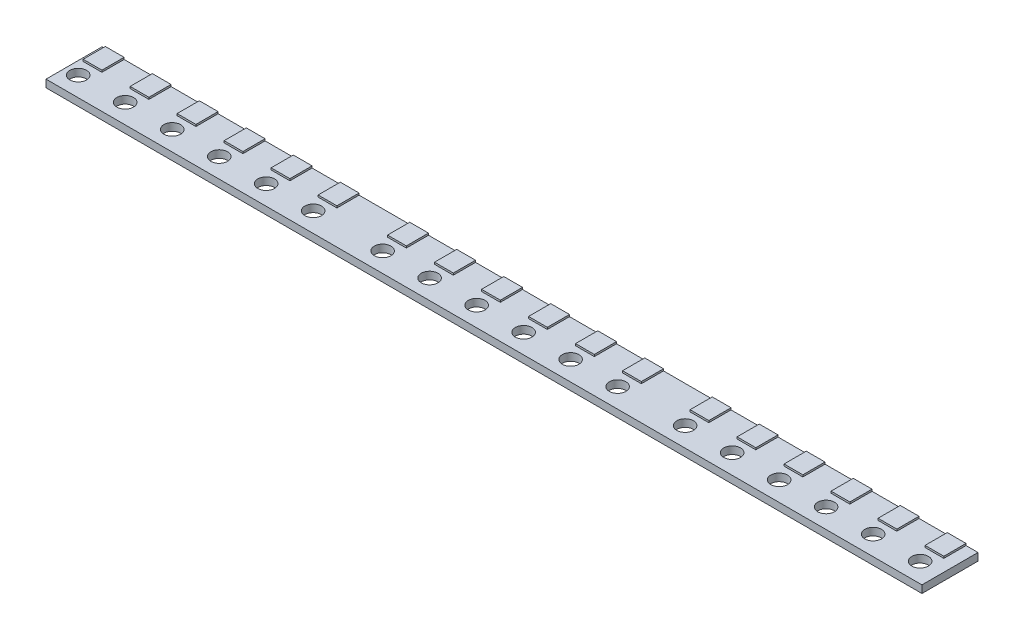
SolidWorks part; units mm, degrees
ref_plane "Front" through (0, 0, 0) normal (0, 0, 1) x (1, 0, 0)
ref_plane "Top" through (0, 0, 0) normal (0, 1, 0) x (1, 0, 0)
ref_plane "Right" through (0, 0, 0) normal (1, 0, 0) x (0, 0, -1)
sketch "Sketch1" plane through (0, 0, 0) normal (0, 1, 0) x (1, 0, 0)
  line L1 (0, 0) -> (96.52, 0)
  line L2 (0, 0) -> (0, 8.9916)
  line L3 (0, 8.9916) -> (96.52, 8.9916)
  line L4 (96.52, 0) -> (96.52, 8.9916)
  dimension "D1" = 8.9916
  dimension "D2" = 96.52
extrude "main boss" add sketch "Sketch1" along normal blind 0.8
sketch "Sketch2" plane through (0, 0, 0) normal (0, 1, 0) x (1, 0, 0)
  line L0 (0, 8.9916) -> (0, 0) construction
  line L1 (0, 0) -> (96.52, 0) construction
  line L2 (2.54, 3.9878) -> (7.5438, 3.9878) construction
  line L3 (34.9504, 3.9878) -> (39.9542, 3.9878) construction
  line L4 (67.1576, 3.9878) -> (72.1614, 3.9878) construction
  circle A0 centre (2.54, 3.9878) radius 0.889
  circle A1 centre (7.5438, 3.9878) radius 0.889
  circle A2 centre (12.5476, 3.9878) radius 0.889
  circle A3 centre (17.5514, 3.9878) radius 0.889
  circle A4 centre (22.5552, 3.9878) radius 0.889
  circle A5 centre (27.559, 3.9878) radius 0.889
  circle A6 centre (34.9504, 3.9878) radius 0.889
  circle A7 centre (39.9542, 3.9878) radius 0.889
  circle A8 centre (44.958, 3.9878) radius 0.889
  circle A9 centre (49.9618, 3.9878) radius 0.889
  circle A10 centre (54.9656, 3.9878) radius 0.889
  circle A11 centre (59.9694, 3.9878) radius 0.889
  circle A12 centre (67.1576, 3.9878) radius 0.889
  circle A13 centre (72.1614, 3.9878) radius 0.889
  circle A14 centre (77.1652, 3.9878) radius 0.889
  circle A15 centre (82.169, 3.9878) radius 0.889
  circle A16 centre (87.1728, 3.9878) radius 0.889
  circle A17 centre (92.1766, 3.9878) radius 0.889
  dimension "D1" = 1.778
  dimension "D2" = 2.54
  dimension "D3" = 3.9878
  dimension "D5" = 5.0038
  dimension "D6" = 34.9504
  dimension "D8" = 5.0038
  dimension "D9" = 67.1576
  dimension "D11" = 5.0038
  dimension "D4" = 6
  dimension "D7" = 6
  dimension "D10" = 6
extrude "holes for PNP pins" cut sketch "Sketch2" along normal through all
sketch "Sketch3" plane through (0, 0.8, 0) normal (0, 1, 0) x (1, 0, 0)
  line L0 (6.5438, 8.0518) -> (8.5438, 8.0518)
  line L1 (1.54, 8.0518) -> (3.54, 8.0518)
  line L2 (1.54, 8.0518) -> (1.54, 5.5118)
  line L3 (1.54, 5.5118) -> (3.54, 5.5118)
  line L4 (3.54, 8.0518) -> (3.54, 5.5118)
  line L5 (33.9504, 8.0518) -> (35.9504, 8.0518)
  line L6 (33.9504, 8.0518) -> (33.9504, 5.5118)
  line L7 (33.9504, 5.5118) -> (35.9504, 5.5118)
  line L8 (35.9504, 8.0518) -> (35.9504, 5.5118)
  line L9 (66.1576, 8.0518) -> (68.1576, 8.0518)
  line L10 (66.1576, 8.0518) -> (66.1576, 5.5118)
  line L11 (66.1576, 5.5118) -> (68.1576, 5.5118)
  line L12 (68.1576, 8.0518) -> (68.1576, 5.5118)
  line L13 (6.5438, 8.0518) -> (6.5438, 5.5118)
  line L14 (6.5438, 5.5118) -> (8.5438, 5.5118)
  line L15 (8.5438, 8.0518) -> (8.5438, 5.5118)
  line L16 (11.5476, 8.0518) -> (13.5476, 8.0518)
  line L17 (11.5476, 8.0518) -> (11.5476, 5.5118)
  line L18 (11.5476, 5.5118) -> (13.5476, 5.5118)
  line L19 (13.5476, 8.0518) -> (13.5476, 5.5118)
  line L20 (16.5514, 8.0518) -> (18.5514, 8.0518)
  line L21 (16.5514, 8.0518) -> (16.5514, 5.5118)
  line L22 (16.5514, 5.5118) -> (18.5514, 5.5118)
  line L23 (18.5514, 8.0518) -> (18.5514, 5.5118)
  line L24 (21.5552, 8.0518) -> (23.5552, 8.0518)
  line L25 (21.5552, 8.0518) -> (21.5552, 5.5118)
  line L26 (21.5552, 5.5118) -> (23.5552, 5.5118)
  line L27 (23.5552, 8.0518) -> (23.5552, 5.5118)
  line L28 (26.559, 8.0518) -> (28.559, 8.0518)
  line L29 (26.559, 8.0518) -> (26.559, 5.5118)
  line L30 (26.559, 5.5118) -> (28.559, 5.5118)
  line L31 (28.559, 8.0518) -> (28.559, 5.5118)
  line L32 (1.54, 8.0518) -> (6.5438, 8.0518) construction
  line L33 (38.9542, 8.0518) -> (40.9542, 8.0518)
  line L34 (38.9542, 8.0518) -> (38.9542, 5.5118)
  line L35 (38.9542, 5.5118) -> (40.9542, 5.5118)
  line L36 (40.9542, 8.0518) -> (40.9542, 5.5118)
  line L37 (43.958, 8.0518) -> (45.958, 8.0518)
  line L38 (43.958, 8.0518) -> (43.958, 5.5118)
  line L39 (43.958, 5.5118) -> (45.958, 5.5118)
  line L40 (45.958, 8.0518) -> (45.958, 5.5118)
  line L41 (48.9618, 8.0518) -> (50.9618, 8.0518)
  line L42 (48.9618, 8.0518) -> (48.9618, 5.5118)
  line L43 (48.9618, 5.5118) -> (50.9618, 5.5118)
  line L44 (50.9618, 8.0518) -> (50.9618, 5.5118)
  line L45 (53.9656, 8.0518) -> (55.9656, 8.0518)
  line L46 (53.9656, 8.0518) -> (53.9656, 5.5118)
  line L47 (53.9656, 5.5118) -> (55.9656, 5.5118)
  line L48 (55.9656, 8.0518) -> (55.9656, 5.5118)
  line L49 (58.9694, 8.0518) -> (60.9694, 8.0518)
  line L50 (58.9694, 8.0518) -> (58.9694, 5.5118)
  line L51 (58.9694, 5.5118) -> (60.9694, 5.5118)
  line L52 (60.9694, 8.0518) -> (60.9694, 5.5118)
  line L53 (33.9504, 8.0518) -> (38.9542, 8.0518) construction
  line L54 (71.1614, 8.0518) -> (73.1614, 8.0518)
  line L55 (71.1614, 8.0518) -> (71.1614, 5.5118)
  line L56 (71.1614, 5.5118) -> (73.1614, 5.5118)
  line L57 (73.1614, 8.0518) -> (73.1614, 5.5118)
  line L58 (76.1652, 8.0518) -> (78.1652, 8.0518)
  line L59 (76.1652, 8.0518) -> (76.1652, 5.5118)
  line L60 (76.1652, 5.5118) -> (78.1652, 5.5118)
  line L61 (78.1652, 8.0518) -> (78.1652, 5.5118)
  line L62 (81.169, 8.0518) -> (83.169, 8.0518)
  line L63 (81.169, 8.0518) -> (81.169, 5.5118)
  line L64 (81.169, 5.5118) -> (83.169, 5.5118)
  line L65 (83.169, 8.0518) -> (83.169, 5.5118)
  line L66 (86.1728, 8.0518) -> (88.1728, 8.0518)
  line L67 (86.1728, 8.0518) -> (86.1728, 5.5118)
  line L68 (86.1728, 5.5118) -> (88.1728, 5.5118)
  line L69 (88.1728, 8.0518) -> (88.1728, 5.5118)
  line L70 (91.1766, 8.0518) -> (93.1766, 8.0518)
  line L71 (91.1766, 8.0518) -> (91.1766, 5.5118)
  line L72 (91.1766, 5.5118) -> (93.1766, 5.5118)
  line L73 (93.1766, 8.0518) -> (93.1766, 5.5118)
  line L74 (66.1576, 8.0518) -> (71.1614, 8.0518) construction
  circle A1 centre (2.54, 3.9878) radius 0.5024 construction
  circle A2 centre (2.54, 3.9878) radius 0.889 construction
  circle A3 centre (34.9504, 3.9878) radius 0.5024 construction
  circle A4 centre (67.1576, 3.9878) radius 0.5024 construction
  circle A5 centre (34.9504, 3.9878) radius 0.889 construction
  circle A6 centre (67.1576, 3.9878) radius 0.889 construction
  point P17 (2.54, 5.5118)
  point P27 (67.1576, 5.5118)
  point P29 (34.9504, 5.5118)
  point P30 (1.54, 6.7818)
  dimension "D1" = 2
  dimension "D2" = 2.54
  dimension "D3" = 2.794
  dimension "D5" = 5.0038
  dimension "D7" = 5.0038
  dimension "D9" = 5.0038
  dimension "D4" = 6
  dimension "D6" = 6
  dimension "D8" = 6
extrude "locator tabs" add sketch "Sketch3" along normal blind 0.2
sketch "Sketch4" plane through (0, 0, 0) normal (0, 1, 0) x (1, 0, 0)
  line L0 (0, 0) -> (96.52, 0) construction
  line L1 (1.1946, 1.905) -> (94.4506, 1.905)
  line L2 (1.1946, 1.905) -> (1.1946, 7.874)
  line L3 (1.1946, 7.874) -> (94.4506, 7.874)
  line L4 (94.4506, 1.905) -> (94.4506, 7.874)
  line L5 (-2.6144, 10.4235) -> (98.588, 10.4235)
  line L6 (-2.6144, 10.4235) -> (-2.6144, -2.6455)
  line L7 (-2.6144, -2.6455) -> (98.588, -2.6455)
  line L8 (98.588, 10.4235) -> (98.588, -2.6455)
  dimension "D1" = 1.905
  dimension "D2" = 7.874
extrude "crop" cut sketch "Sketch4" along normal through all
